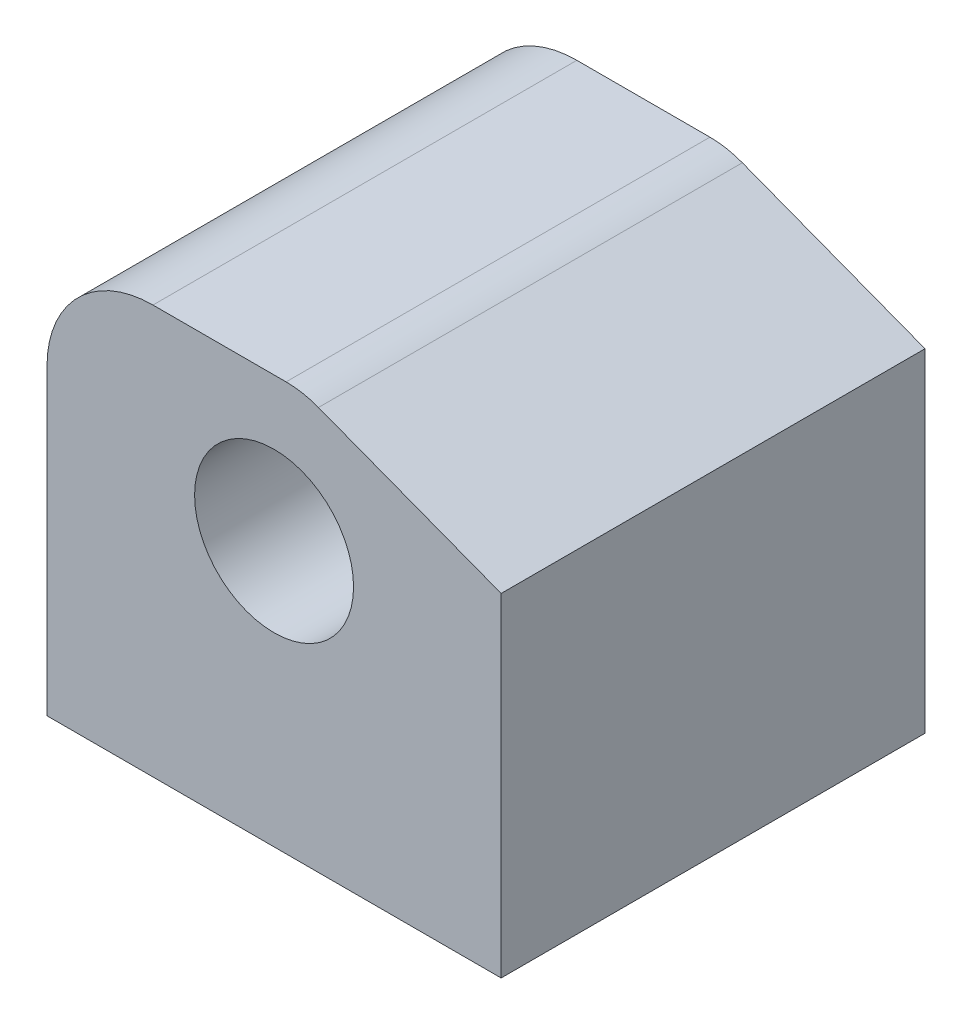
SolidWorks part; units mm, degrees
ref_plane "Płaszczyzna przednia" through (0, 0, 0) normal (0, 0, 1) x (1, 0, 0)
ref_plane "Płaszczyzna górna" through (0, 0, 0) normal (0, 1, 0) x (1, 0, 0)
ref_plane "Płaszczyzna prawa" through (0, 0, 0) normal (1, 0, 0) x (0, 0, -1)
sketch "Szkic1" plane through (0, 0, 0) normal (0, 1, 0) x (1, 0, 0)
  line L1 (-7.5, -7) -> (7.5, -7)
  line L2 (-7.5, -7) -> (-7.5, 7)
  line L3 (-7.5, 7) -> (7.5, 7)
  line L4 (7.5, -7) -> (7.5, 7)
  line L5 (-7.5, -7) -> (7.5, 7) construction
  line L6 (-7.5, 7) -> (7.5, -7) construction
  point P0 (0, 0)
  dimension "D1" = 14
  dimension "D2" = 15
extrude "Dodanie-wyciągnięcie1" add sketch "Szkic1" along normal blind 13.5
sketch "Szkic2" plane through (0, 0, 7) normal (0, 0, 1) x (1, 0, 0)
  line L0 (7.5, 0) -> (0, 0) construction
  line L1 (-7.5, 0) -> (7.5, 0) construction
  line L2 (0, 0) -> (0, 8.75) construction
  circle A0 centre (0, 8.75) radius 2.625
  dimension "D3" = 5.25
  dimension "D1" = 7.5
  dimension "D2" = 8.75
extrude "Wytnij-wyciągnięcie1" cut sketch "Szkic2" against normal blind 15
fillet "Zaokrąglenie1" radius 3.5 1 edges at (-7.5, 13.5, 0)
sketch "Szkic3" plane through (0, 0, 7) normal (0, 0, 1) x (1, 0, 0)
  line L0 (7.5, 0) -> (7.5, 11) construction
  line L1 (7.5, 13.5) -> (7.5, 0) construction
  line L2 (7.5, 0) -> (7.5, 13.5) construction
  line L3 (7.5, 13.5) -> (0.95, 13.5) construction
  line L4 (-4, 13.5) -> (7.5, 13.5) construction
  line L5 (0.95, 13.5) -> (7.5, 11)
  line L6 (7.5, 11) -> (7.5, 13.5)
  line L7 (7.5, 13.5) -> (0.95, 13.5)
  dimension "D1" = 11
  dimension "D2" = 6.55
extrude "Wytnij-wyciągnięcie2" cut sketch "Szkic3" against normal blind 15
fillet "Zaokrąglenie2" radius 3 1 edges at (0.95, 13.5, 0)
sketch "Szkic4" plane through (0, 0, 0) normal (0, -1, 0) x (1, 0, 0)
  line L0 (-7.5, 7) -> (0, 7) construction
  line L1 (-7.5, 7) -> (7.5, 7) construction
  line L2 (0, 7) -> (0, 0) construction
  circle A0 centre (0, 0) radius 5.5
  dimension "D1" = 11
extrude "Wytnij-wyciągnięcie3" cut sketch "Szkic4" against normal blind 3
